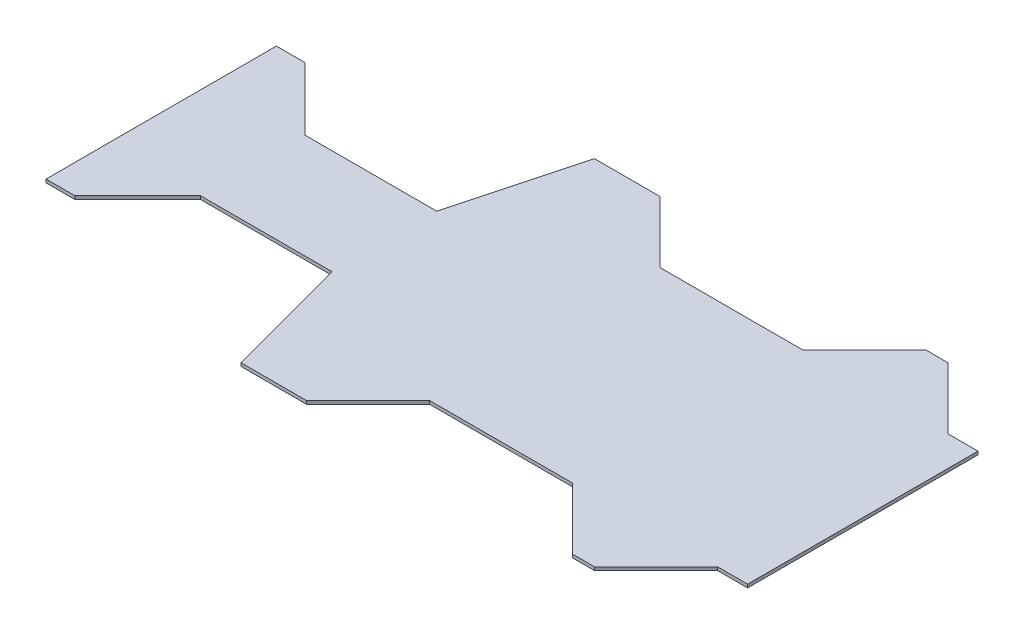
SolidWorks part; units mm, degrees
ref_plane "Front Plane" through (0, 0, 0) normal (0, 0, 1) x (1, 0, 0)
ref_plane "Top Plane" through (0, 0, 0) normal (0, 1, 0) x (1, 0, 0)
ref_plane "Right Plane" through (0, 0, 0) normal (1, 0, 0) x (0, 0, -1)
other "avc2012"
sketch "Sketch1" plane through (0, 0, 0) normal (0, 1, 0) x (1, 0, 0)
  line L0 (125.73, -85.725) -> (115.1774, -85.725)
  line L1 (-170.18, 0) -> (170.18, 0) construction
  line L2 (-170.18, -55.88) -> (-170.18, 55.88)
  line L3 (-170.18, -55.88) -> (-156.21, -55.88)
  line L4 (170.18, -55.88) -> (170.18, 55.88)
  line L5 (115.1774, -85.725) -> (85.3324, -55.88)
  line L6 (85.3324, -55.88) -> (15.875, -55.88)
  line L7 (15.875, -55.88) -> (-13.97, -85.725)
  line L8 (125.73, -85.725) -> (155.575, -55.88)
  line L9 (-45.72, 85.725) -> (-61.884, 25.4)
  line L10 (-156.21, -55.88) -> (-125.73, -25.4)
  line L11 (-125.73, -25.4) -> (-61.884, -25.4)
  line L12 (-13.97, -85.725) -> (-45.72, -85.725)
  line L13 (155.575, -55.88) -> (170.18, -55.88)
  line L14 (-45.72, -85.725) -> (-61.884, -25.4)
  line L15 (155.575, 55.88) -> (170.18, 55.88)
  line L16 (-13.97, 85.725) -> (-45.72, 85.725)
  line L17 (-125.73, 25.4) -> (-61.884, 25.4)
  line L18 (-156.21, 55.88) -> (-125.73, 25.4)
  line L19 (125.73, 85.725) -> (155.575, 55.88)
  line L20 (15.875, 55.88) -> (-13.97, 85.725)
  line L21 (85.3324, 55.88) -> (15.875, 55.88)
  line L22 (115.1774, 85.725) -> (85.3324, 55.88)
  line L23 (-170.18, 55.88) -> (-156.21, 55.88)
  line L24 (125.73, 85.725) -> (115.1774, 85.725)
  dimension "D1" = 340.36
  dimension "D2" = 111.76
  dimension "D3" = 31.75
  dimension "D4" = 50.8
  dimension "D5" = 85.725
  dimension "D6" = 135
  dimension "D7" = 171.45
  dimension "D8" = 135
  dimension "D9" = 135
  dimension "D10" = 105
  dimension "D11" = 44.45
  dimension "D12" = 44.45
extrude "Plate" add sketch "Sketch1" along normal blind 1.5875
